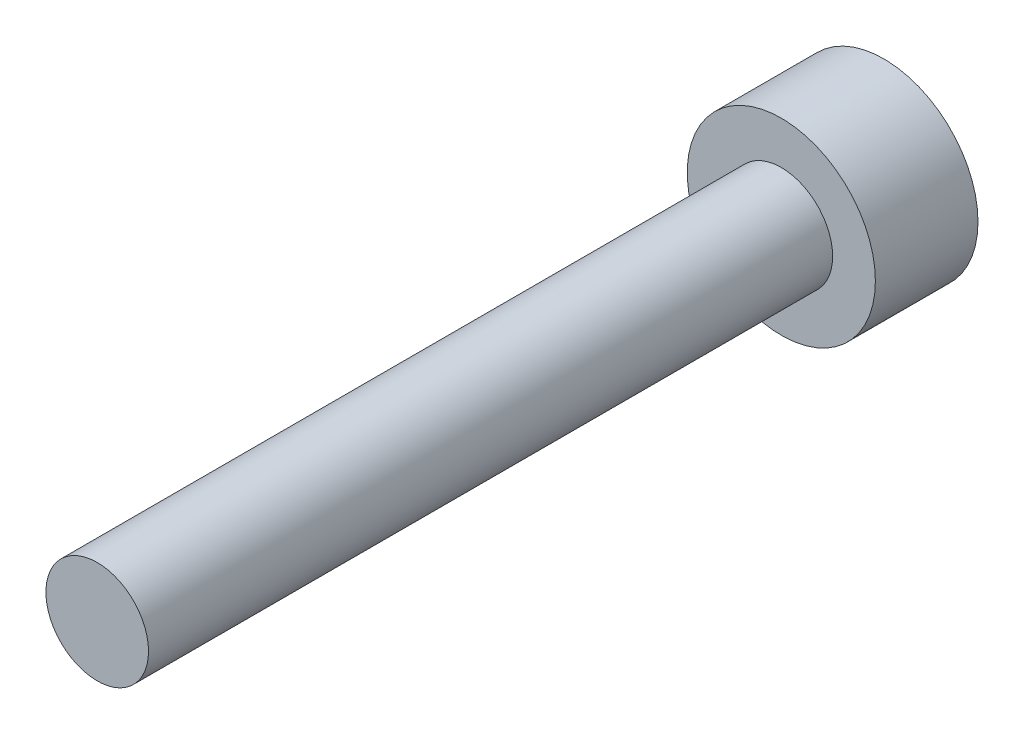
SolidWorks part; units mm, degrees
ref_plane "Front Plane" through (0, 0, 0) normal (0, 0, 1) x (1, 0, 0)
ref_plane "Top Plane" through (0, 0, 0) normal (0, 1, 0) x (1, 0, 0)
ref_plane "Right Plane" through (0, 0, 0) normal (1, 0, 0) x (0, 0, -1)
sketch "S01 - Head" plane through (0, 0, 0) normal (0, 0, 1) x (1, 0, 0)
  circle A0 centre (0, 0) radius 2.75
  dimension "D1" = 5.5
extrude "01 - Head" add sketch "S01 - Head" along normal blind 3 from offset 3
sketch "S02 - Nominal shank" plane through (0, 0, 0) normal (0, 0, 1) x (1, 0, 0)
  circle A0 centre (0, 0) radius 1.5
  dimension "D1" = 3
extrude "02 - Nominal shank" add sketch "S02 - Nominal shank" along normal blind 20
sketch "S03 - Hex key socket" plane through (0, 0, 0) normal (0, 0, 1) x (1, 0, 0)
  line L0 (1.4434, 0) -> (0.7217, 1.25)
  line L1 (0.7217, 1.25) -> (-0.7217, 1.25)
  line L2 (-0.7217, 1.25) -> (-1.4434, 0)
  line L3 (-1.4434, 0) -> (-0.7217, -1.25)
  line L4 (-0.7217, -1.25) -> (0.7217, -1.25)
  line L5 (0.7217, -1.25) -> (1.4434, 0)
  dimension "D1" = 0.7217
  dimension "D2" = 1.4434
  dimension "D3" = 0.7217
  dimension "D4" = 1.4434
  dimension "D5" = 1.25
  dimension "D6" = 1.25
extrude "03 - Hex key socket" cut sketch "S03 - Hex key socket" along normal blind 1.75 from offset 3.1
